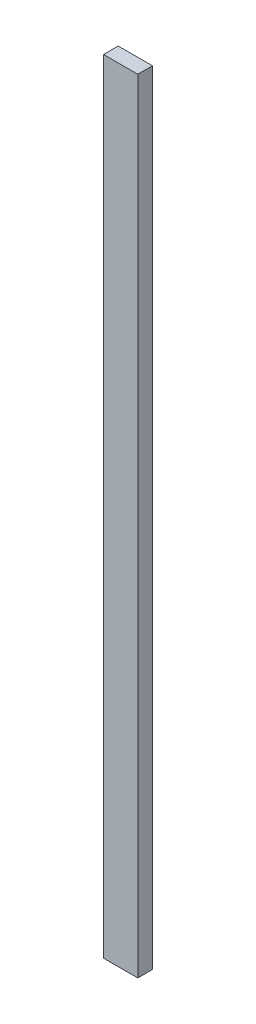
SolidWorks part; units mm, degrees
ref_plane "Front Plane" through (0, 0, 0) normal (0, 0, 1) x (1, 0, 0)
ref_plane "Top Plane" through (0, 0, 0) normal (0, 1, 0) x (1, 0, 0)
ref_plane "Right Plane" through (0, 0, 0) normal (1, 0, 0) x (0, 0, -1)
sketch "Sketch1" plane through (0, 0, 0) normal (0, 1, 0) x (1, 0, 0)
  line L1 (-44.45, -19.05) -> (44.45, -19.05)
  line L2 (-44.45, -19.05) -> (-44.45, 19.05)
  line L3 (-44.45, 19.05) -> (44.45, 19.05)
  line L4 (44.45, -19.05) -> (44.45, 19.05)
  line L5 (-44.45, -19.05) -> (44.45, 19.05) construction
  line L6 (-44.45, 19.05) -> (44.45, -19.05) construction
  point P0 (0, 0)
  dimension "D1" = 88.9
  dimension "D2" = 38.1
extrude "Boss-Extrude1" add sketch "Sketch1" along normal blind 2032
